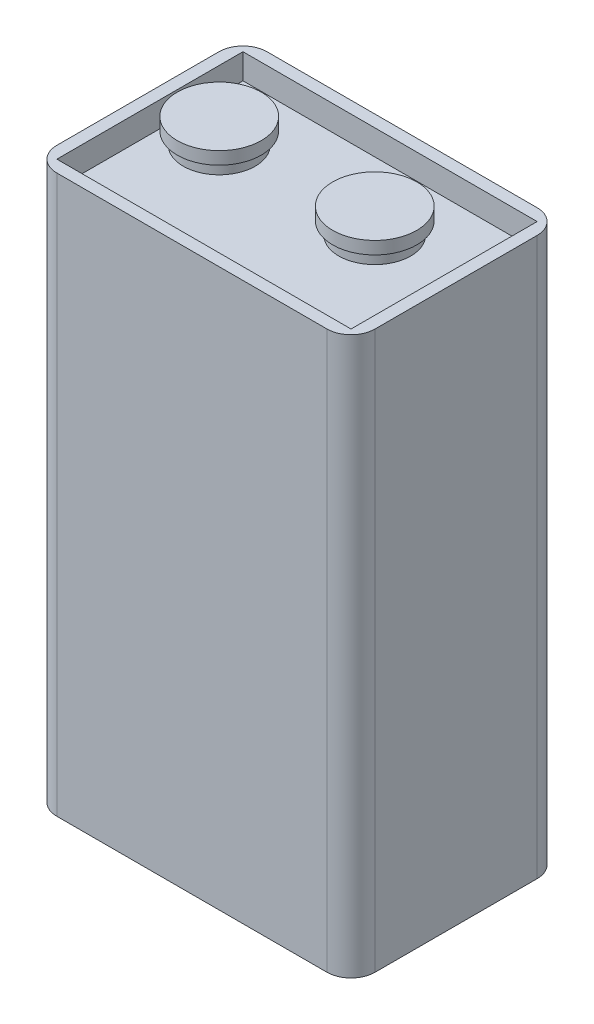
SolidWorks part; units mm, degrees
ref_plane "Front Plane" through (0, 0, 0) normal (0, 0, 1) x (1, 0, 0)
ref_plane "Top Plane" through (0, 0, 0) normal (0, 1, 0) x (1, 0, 0)
ref_plane "Right Plane" through (0, 0, 0) normal (1, 0, 0) x (0, 0, -1)
sketch "Sketch2" plane through (0, 0, 0) normal (0, 1, 0) x (1, 0, 0)
  line L1 (0, 0) -> (26.5, 0)
  line L2 (0, 0) -> (0, 17.5)
  line L3 (0, 17.5) -> (26.5, 17.5)
  line L4 (26.5, 0) -> (26.5, 17.5)
extrude "Boss-Extrude1" add sketch "Sketch2" against normal blind 46.4
sketch "Sketch4" plane through (0, 0, 0) normal (0, 1, 0) x (1, 0, 0)
  circle A0 centre (19.725, 8.75) radius 3
  circle A1 centre (6.775, 8.75) radius 3
  dimension "D1" = 6
  dimension "D2" = 6
extrude "Boss-Extrude5" add sketch "Sketch4" along normal blind 1.05
sketch "Sketch5" plane through (0, 1.05, 0) normal (0, 1, 0) x (1, 0, 0)
  circle A0 centre (6.775, 8.75) radius 3.5
  dimension "D1" = 7
extrude "Boss-Extrude6" add sketch "Sketch5" along normal blind 1.05
sketch "Sketch6" plane through (0, 1.05, 0) normal (0, 1, 0) x (1, 0, 0)
  circle A0 centre (19.725, 8.75) radius 3.5
  dimension "D1" = 7
extrude "Boss-Extrude7" add sketch "Sketch6" along normal blind 1.05
sketch "Sketch7" plane through (0, 0, 0) normal (0, 0, 1) x (1, 0, 0)
  text T0 "+"
  text T1 "-"
sketch "Sketch9" plane through (0, 0, 0) normal (0, 1, 0) x (1, 0, 0)
  line L12 (1, 16.5) -> (25.5, 16.5)
  line L13 (25.5, 1) -> (25.5, 16.5)
  line L14 (1, 1) -> (25.5, 1)
  line L15 (1, 1) -> (1, 16.5)
extrude "Cut-Extrude2" cut sketch "Sketch9" against normal blind 2.1
fillet "Fillet1" radius 2 1 edges at (26.5, -23.2, 0)
fillet "Fillet2" radius 2 1 edges at (26.5, -23.2, -17.5)
fillet "Fillet3" radius 2 1 edges at (0, -23.2, -17.5)
fillet "Fillet4" radius 2 1 edges at (0, -23.2, 0)
